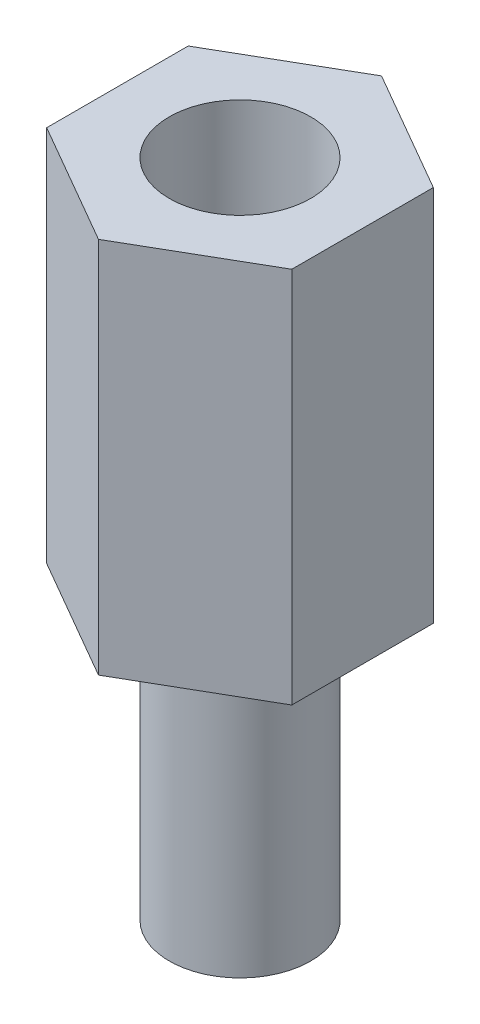
SolidWorks part; units mm, degrees
ref_plane "Alzado" through (0, 0, 0) normal (0, 0, 1) x (1, 0, 0)
ref_plane "Planta" through (0, 0, 0) normal (0, 1, 0) x (1, 0, 0)
ref_plane "Vista lateral" through (0, 0, 0) normal (1, 0, 0) x (0, 0, -1)
sketch "Croquis1" plane through (0, 0, 0) normal (0, 1, 0) x (1, 0, 0)
  line L0 (-2.5981, 1.5) -> (2.5981, -1.5) construction
  line L1 (0, 3) -> (0, -3) construction
  line L2 (2.5981, 1.5) -> (-2.5981, -1.5) construction
  line L3 (-2.5981, 1.5) -> (-2.5981, -1.5)
  line L4 (-2.5981, -1.5) -> (0, -3)
  line L5 (0, -3) -> (2.5981, -1.5)
  line L6 (2.5981, -1.5) -> (2.5981, 1.5)
  line L7 (2.5981, 1.5) -> (0, 3)
  line L8 (0, 3) -> (-2.5981, 1.5)
  line L9 (0, 0) -> (0, 1.9342) construction
  circle A0 centre (0, 0) radius 3 construction
  dimension "D1" = 6
  dimension "D2" = 60
  dimension "D3" = 60
extrude "Saliente-Extruir1" add sketch "Croquis1" along normal blind 8 contours L4 L5 L6 L7 L8 L3
sketch "Croquis2" plane through (0, 0, 0) normal (0, -1, 0) x (1, 0, 0)
  circle A0 centre (0, 0) radius 1.5
  dimension "D1" = 3
extrude "Saliente-Extruir2" add sketch "Croquis2" along normal blind 6
sketch "Croquis3" plane through (0, 8, 0) normal (0, 1, 0) x (1, 0, 0)
  circle A0 centre (0, 0) radius 1.5
  dimension "D1" = 3
extrude "Cortar-Extruir1" cut sketch "Croquis3" against normal blind 6
